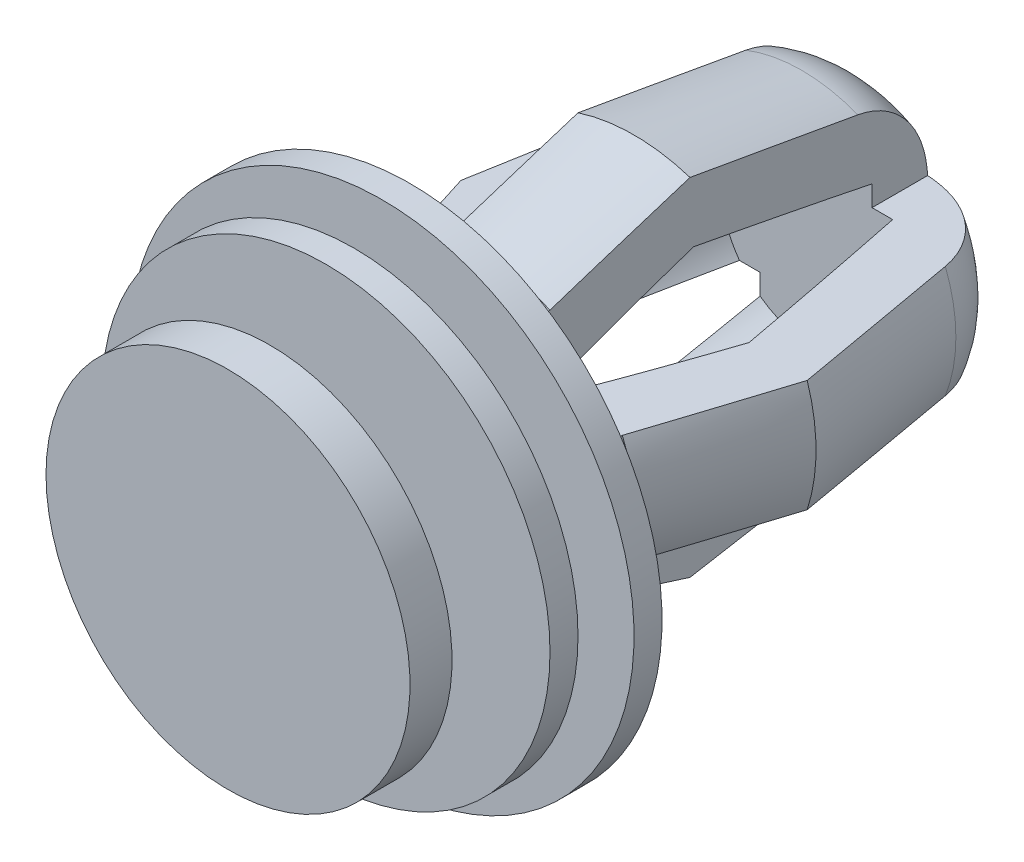
SolidWorks part; units mm, degrees
ref_plane "正面" through (0, 0, 0) normal (0, 0, 1) x (1, 0, 0)
ref_plane "平面" through (0, 0, 0) normal (0, 1, 0) x (1, 0, 0)
ref_plane "右側面" through (0, 0, 0) normal (1, 0, 0) x (0, 0, -1)
sketch "ｽｹｯﾁ1" plane through (0, 0, 0) normal (1, 0, 0) x (0, 0, -1)
  line L0 (0, 0) -> (-92.9851, 0) construction
  line L1 (0, 7.5) -> (2, 7.5)
  line L2 (2, 7.5) -> (5, 8.5)
  line L3 (5, 8.5) -> (22, 6)
  line L4 (22, 6) -> (22, 0)
  line L5 (22, 0) -> (15.5, 0)
  line L6 (15.5, 0) -> (15.5, 5)
  line L7 (1.5, 5) -> (-1.5, 5)
  line L8 (-1.5, 5) -> (-1.5, 11.5)
  line L9 (-1.5, 11.5) -> (0, 11.5)
  line L10 (0, 11.5) -> (0, 7.5)
  line L11 (1.5, 5) -> (6.5, 6.5)
  line L12 (6.5, 6.5) -> (15.5, 5)
  dimension "D1" = 15
  dimension "D2" = 23
  dimension "D3" = 1.5
  dimension "D4" = 10
  dimension "D5" = 17
  dimension "D6" = 22
  dimension "D7" = 12
  dimension "D8" = 17
  dimension "D9" = 2
  dimension "D10" = 5
  dimension "D11" = 3
  dimension "D12" = 5
  dimension "D13" = 13
  dimension "D14" = 10
sketch "ｽｹｯﾁ3" plane through (0, 0, 0) normal (1, 0, 0) x (0, 0, -1)
  line L0 (0, 0) -> (-46.4925, 0) construction
  line L1 (0, 0) -> (-92.9851, 0) construction
  line L2 (-1.5, 5) -> (1.5, 5)
  line L3 (1.5, 5) -> (6.5, 6.5)
  line L4 (6.5, 6.5) -> (15, 5.0833)
  line L5 (15, 5.0833) -> (15, 0)
  line L6 (15, 0) -> (13, 0)
  line L7 (-8, 0) -> (-8, 6.5)
  line L8 (-8, 6.5) -> (-6.5, 6.5)
  line L9 (-6.5, 6.5) -> (-6.5, 3.5)
  line L10 (-6.5, 3.5) -> (-4.5, 3.5)
  line L11 (-4.5, 3.5) -> (-4.5, 8)
  line L12 (-4.5, 8) -> (-3.5, 8)
  line L13 (-3.5, 8) -> (-3.5, 3.5)
  line L14 (-3.5, 3.5) -> (-2.5, 3.5)
  line L15 (-2.5, 3.5) -> (-2.5, 9)
  line L16 (-2.5, 9) -> (-1.5, 9)
  line L17 (-1.5, 9) -> (-1.5, 5)
  line L18 (-1.5, 0) -> (-1.5, 3)
  line L19 (-1.5, 3) -> (1.7935, 3)
  line L20 (13, 3.3891) -> (13, 0)
  line L21 (-1.5, 0) -> (-8, 0)
  line L22 (1.7935, 3) -> (6.6296, 4.4508)
  line L23 (6.6296, 4.4508) -> (13, 3.3891)
  point P30 (-2, 9)
  point P31 (-3.5, 5.75)
  dimension "D1" = 15
  dimension "D2" = 13
  dimension "D3" = 16
  dimension "D4" = 7
  dimension "D5" = 18
  dimension "D6" = 1
  dimension "D7" = 1
  dimension "D8" = 1
  dimension "D9" = 2
  dimension "D10" = 1.5
  dimension "D11" = 2
  dimension "D12" = 2
  dimension "D13" = 2
  dimension "D14" = 2
revolve "回転2" add sketch "ｽｹｯﾁ3" angle 360 about L0
fillet "ﾌｨﾚｯﾄ2" radius 3 1 edges at (-5.0833, 0, -15)
sketch "ｽｹｯﾁ4" plane through (0, 0, -15) normal (0, 0, -1) x (-1, 0, 0)
  line L1 (-2, 2) -> (-14.0837, 2)
  line L2 (-2, 2) -> (-2, 13.5426)
  line L3 (-2, 13.5426) -> (-14.0837, 13.5426)
  line L4 (-14.0837, 2) -> (-14.0837, 13.5426)
  dimension "D1" = 2
  dimension "D2" = 2
extrude "ｶｯﾄ - 押し出し2" cut sketch "ｽｹｯﾁ4" against normal up to surface (16.5 mm away) up to face at (-9, 0, 1.5)
pattern_circular "円形ﾊﾟﾀｰﾝ2" count 4 over 360 about axis through (0, 0, 0) along (0, 0, 1) of "ｶｯﾄ - 押し出し2"
